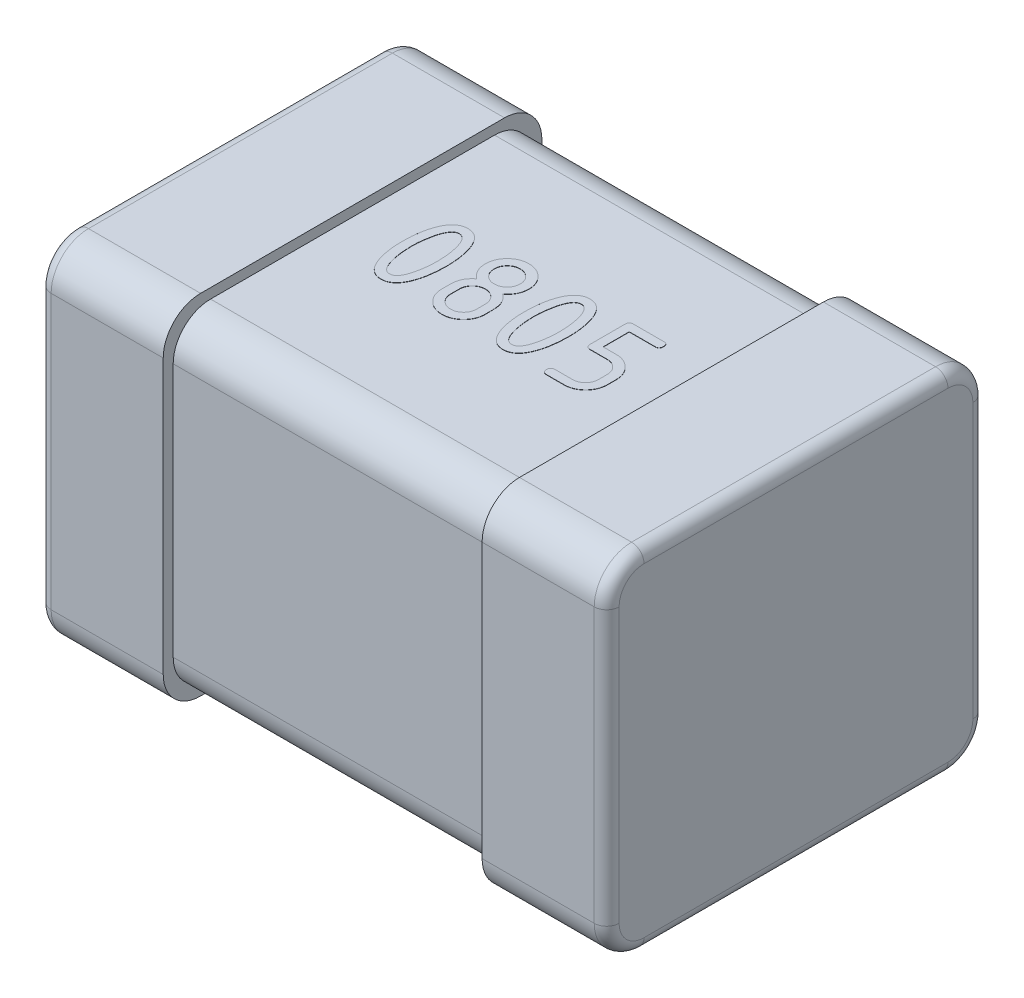
SolidWorks part; units mm, degrees
ref_plane "Front" through (0, 0, 0) normal (0, 0, 1) x (1, 0, 0)
ref_plane "Top" through (0, 0, 0) normal (0, 1, 0) x (1, 0, 0)
ref_plane "Right" through (0, 0, 0) normal (1, 0, 0) x (0, 0, -1)
sketch "Sketch1" plane through (0, 0, 0) normal (0, 1, 0) x (1, 0, 0)
  line L1 (-1.14, -0.76) -> (1.14, -0.76)
  line L2 (-1.14, -0.76) -> (-1.14, 0.76)
  line L3 (-1.14, 0.76) -> (1.14, 0.76)
  line L4 (1.14, -0.76) -> (1.14, 0.76)
  line L5 (-1.14, -0.76) -> (1.14, 0.76) construction
  line L6 (-1.14, 0.76) -> (1.14, -0.76) construction
  point P0 (0, 0)
  dimension "D1" = 1.52
  dimension "D2" = 2.28
extrude "Boss-Extrude1" add sketch "Sketch1" along normal mid plane 1.4
sketch "Sketch3" plane through (0, 0, 0) normal (1, 0, 0) x (0, 0, -1)
  line L8 (-0.72, -0.66) -> (0.72, -0.66)
  line L9 (0.72, -0.66) -> (0.72, 0.66)
  line L10 (0.72, 0.66) -> (-0.72, 0.66)
  line L11 (-0.72, 0.66) -> (-0.72, -0.66)
  line L12 (-0.72, -0.66) -> (0.72, -0.66)
  line L13 (0.72, -0.66) -> (0.72, 0.66)
  line L14 (0.72, 0.66) -> (-0.72, 0.66)
  line L15 (-0.72, 0.66) -> (-0.72, -0.66)
  dimension "D1" = 0.04
extrude "Cut-Extrude1" cut sketch "Sketch3" against normal offset from surface 0.5 and the other way offset from surface (0.64 mm away) 0.5 flip side to cut up to face at (-1.14, 0, 0) other way up to face at (1.14, 0, 0)
fillet "Fillet1" radius 0.15 4 edges at (0, -0.66, -0.72) (0, 0.66, -0.72) (0, -0.66, 0.72) (0, 0.66, 0.72)
fillet "Fillet2" radius 0.15 8 edges at (-0.89, -0.7, 0.76) (-0.89, 0.7, 0.76) (0.89, 0.7, 0.76) (0.89, -0.7, 0.76) (-0.89, -0.7, -0.76) (-0.89, 0.7, -0.76) (0.89, 0.7, -0.76) (0.89, -0.7, -0.76)
fillet "Fillet3" radius 0.05 16 edges at (1.14, 0.6561, -0.7161) (1.14, 0, -0.76) (1.14, -0.6561, -0.7161) (1.14, -0.7, 0) (1.14, -0.6561, 0.7161) (1.14, 0, 0.76) (1.14, 0.6561, 0.7161) (1.14, 0.7, 0) (-1.14, -0.6561, -0.7161) (-1.14, 0, -0.76) (-1.14, 0.6561, -0.7161) (-1.14, 0.7, 0) (-1.14, 0.6561, 0.7161) (-1.14, 0, 0.76) (-1.14, -0.6561, 0.7161) (-1.14, -0.7, 0)
sketch "Sketch4" plane through (0, 0.66, 0) normal (0, 1, 0) x (1, 0, 0)
  line L0 (-0.64, -0.1592) -> (0.64, -0.1592) construction
  line L1 (-0.64, -0.57) -> (-0.64, 0.57) construction
  line L2 (0.64, -0.61) -> (0.64, 0.61) construction
  text T0 "0805" font "ISOCPEUR" height 0.35
extrude "Boss-Extrude2" add sketch "Sketch4" along normal blind 0.001
